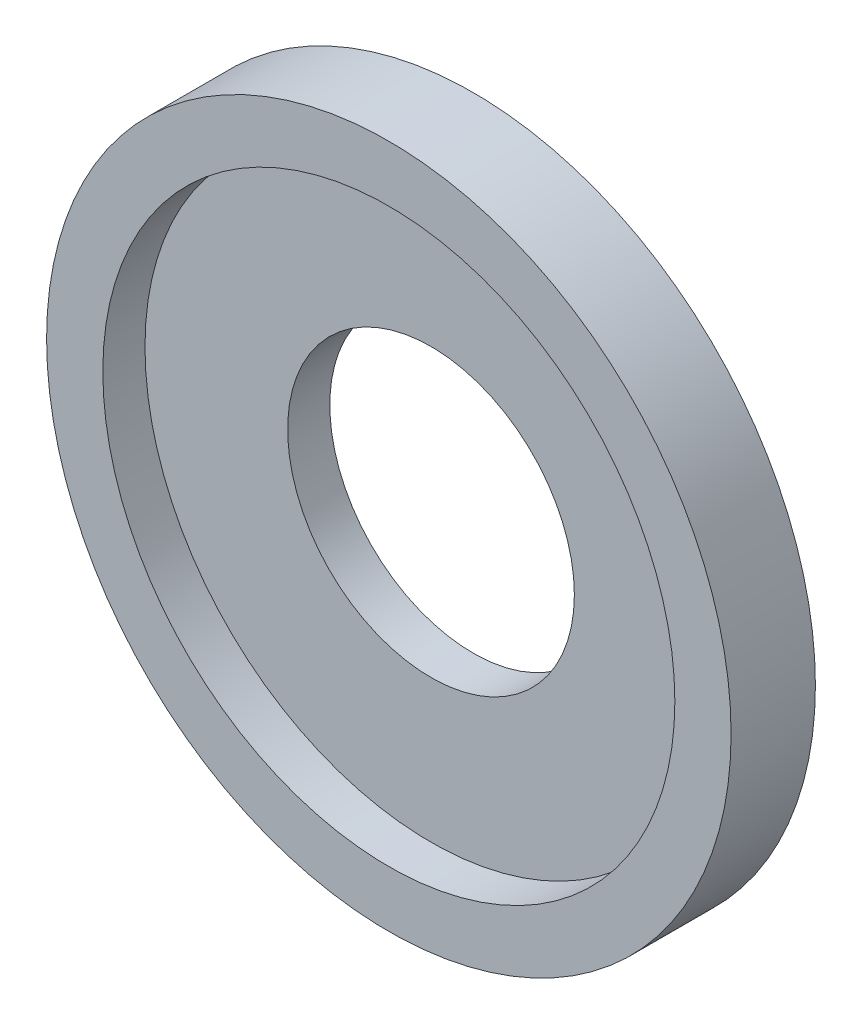
SolidWorks part; units mm, degrees
ref_plane "Front Plane" through (0, 0, 0) normal (0, 0, 1) x (1, 0, 0)
ref_plane "Top Plane" through (0, 0, 0) normal (0, 1, 0) x (1, 0, 0)
ref_plane "Right Plane" through (0, 0, 0) normal (1, 0, 0) x (0, 0, -1)
sketch "Sketch1" plane through (0, 0, 0) normal (0, 0, 1) x (1, 0, 0)
  circle A0 centre (0, 0) radius 10.175
  circle A1 centre (0, 0) radius 12.175
  dimension "D1" = 20.35
  dimension "D2" = 2
extrude "Boss-Extrude1" add sketch "Sketch1" along normal blind 3
sketch "Sketch2" plane through (0, 0, 0) normal (0, 0, 1) x (1, 0, 0)
  circle A0 centre (0, 0) radius 12.175
  circle A1 centre (0, 0) radius 5.1
  dimension "D1" = 24.35
  dimension "D2" = 10.2
extrude "Boss-Extrude2" add sketch "Sketch2" along normal blind 1.5
